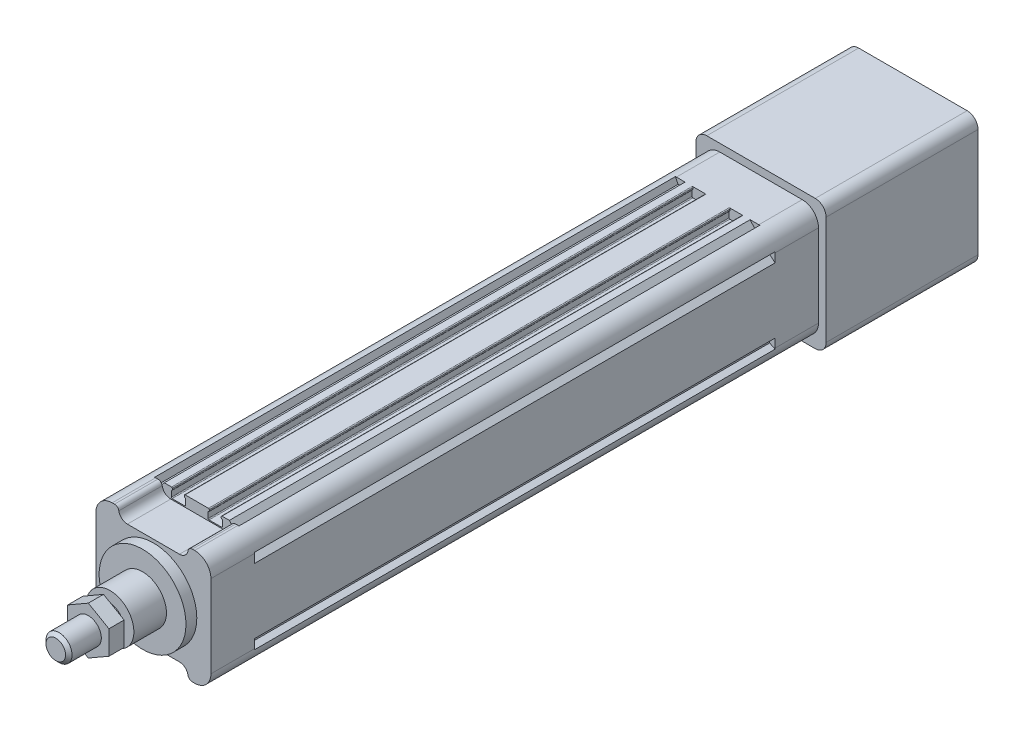
SolidWorks part; units mm, degrees
ref_plane "Front" through (0, 0, 0) normal (0, 0, 1) x (1, 0, 0)
ref_plane "Top" through (0, 0, 0) normal (0, 1, 0) x (1, 0, 0)
ref_plane "Right" through (0, 0, 0) normal (1, 0, 0) x (0, 0, -1)
sketch "草图1" plane through (0, 0, 0) normal (0, 0, 1) x (1, 0, 0)
  line L0 (19.7737, 3) -> (23.3, 3)
  line L1 (23.3, 3) -> (23.3, -3)
  line L2 (23.3, -3) -> (19.7737, -3)
  line L3 (-19.7737, -3) -> (-23.3, -3)
  line L4 (-23.3, -3) -> (-23.3, 3)
  line L5 (-23.3, 3) -> (-19.7737, 3)
  line L6 (-18.2, 24) -> (-19.4434, 26.4869)
  line L7 (-26.4869, 19.4434) -> (-24, 18.2)
  line L8 (-24, 18.2) -> (-24, 17.1)
  line L9 (-24, 17.1) -> (-26.5, 15)
  line L10 (-26.5, 15) -> (-26.5, -15)
  line L11 (-26.5, -15) -> (-24, -17.1)
  line L12 (-24, -17.1) -> (-24, -18.2)
  line L13 (-24, -18.2) -> (-26.4869, -19.4434)
  line L14 (-19.4434, -26.4869) -> (-18.2, -24)
  line L15 (-18.2, -24) -> (-17.1, -24)
  line L16 (-17.1, -24) -> (-15, -26.5)
  line L17 (-15, -26.5) -> (-11.65, -26.5)
  line L18 (-11.25, -26.1) -> (-11.25, -25.6)
  line L19 (-11.65, -25.2) -> (-11.75, -25.2)
  line L20 (-11.75, -25.2) -> (-11.75, -22.4)
  line L21 (-11.35, -22) -> (-5.65, -22)
  line L22 (-5.25, -22.4) -> (-5.25, -25.2)
  line L23 (-5.25, -25.2) -> (-5.35, -25.2)
  line L24 (-5.75, -25.6) -> (-5.75, -26.1)
  line L25 (-5.35, -26.5) -> (5.35, -26.5)
  line L26 (5.75, -26.1) -> (5.75, -25.6)
  line L27 (5.35, -25.2) -> (5.25, -25.2)
  line L28 (5.25, -25.2) -> (5.25, -22.4)
  line L29 (5.65, -22) -> (11.35, -22)
  line L30 (11.75, -22.4) -> (11.75, -25.2)
  line L31 (11.75, -25.2) -> (11.65, -25.2)
  line L32 (11.25, -25.6) -> (11.25, -26.1)
  line L33 (11.65, -26.5) -> (15, -26.5)
  line L34 (15, -26.5) -> (17.1, -24)
  line L35 (17.1, -24) -> (18.2, -24)
  line L36 (18.2, -24) -> (19.4434, -26.4869)
  line L37 (26.4869, -19.4434) -> (24, -18.2)
  line L38 (24, -18.2) -> (24, -17.1)
  line L39 (24, -17.1) -> (26.5, -15)
  line L40 (26.5, -15) -> (26.5, 15)
  line L41 (26.5, 15) -> (24, 17.1)
  line L42 (24, 17.1) -> (24, 18.2)
  line L43 (24, 18.2) -> (26.4869, 19.4434)
  line L44 (19.4434, 26.4869) -> (18.2, 24)
  line L45 (18.2, 24) -> (17.1, 24)
  line L46 (17.1, 24) -> (15, 26.5)
  line L47 (15, 26.5) -> (11.65, 26.5)
  line L48 (11.25, 26.1) -> (11.25, 25.6)
  line L49 (11.65, 25.2) -> (11.75, 25.2)
  line L50 (11.75, 25.2) -> (11.75, 22.4)
  line L51 (11.35, 22) -> (5.65, 22)
  line L52 (5.25, 22.4) -> (5.25, 25.2)
  line L53 (5.25, 25.2) -> (5.35, 25.2)
  line L54 (5.75, 25.6) -> (5.75, 26.1)
  line L55 (5.35, 26.5) -> (-5.35, 26.5)
  line L56 (-5.75, 26.1) -> (-5.75, 25.6)
  line L57 (-5.35, 25.2) -> (-5.25, 25.2)
  line L58 (-5.25, 25.2) -> (-5.25, 22.4)
  line L59 (-5.65, 22) -> (-11.35, 22)
  line L60 (-11.75, 22.4) -> (-11.75, 25.2)
  line L61 (-11.75, 25.2) -> (-11.65, 25.2)
  line L62 (-11.25, 25.6) -> (-11.25, 26.1)
  line L63 (-11.65, 26.5) -> (-15, 26.5)
  line L64 (-15, 26.5) -> (-17.1, 24)
  line L65 (-17.1, 24) -> (-18.2, 24)
  arc A0 (19.7737, 3) -> (-19.7737, 3) centre (0, 0) ccw
  arc A1 (-19.7737, -3) -> (19.7737, -3) centre (0, 0) ccw
  circle A2 centre (19, 19) radius 2.1
  circle A3 centre (19, -19) radius 2.1
  circle A4 centre (-19, -19) radius 2.1
  circle A5 centre (-19, 19) radius 2.1
  arc A6 (-19.4434, 26.4869) -> (-26.4869, 19.4434) centre (-19, 19) ccw
  arc A7 (-26.4869, -19.4434) -> (-19.4434, -26.4869) centre (-19, -19) ccw
  arc A8 (-11.65, -26.5) -> (-11.25, -26.1) centre (-11.65, -26.1) ccw
  arc A9 (-11.25, -25.6) -> (-11.65, -25.2) centre (-11.65, -25.6) ccw
  arc A10 (-11.35, -22) -> (-11.75, -22.4) centre (-11.35, -22.4) ccw
  arc A11 (-5.25, -22.4) -> (-5.65, -22) centre (-5.65, -22.4) ccw
  arc A12 (-5.35, -25.2) -> (-5.75, -25.6) centre (-5.35, -25.6) ccw
  arc A13 (-5.75, -26.1) -> (-5.35, -26.5) centre (-5.35, -26.1) ccw
  arc A14 (5.35, -26.5) -> (5.75, -26.1) centre (5.35, -26.1) ccw
  arc A15 (5.75, -25.6) -> (5.35, -25.2) centre (5.35, -25.6) ccw
  arc A16 (5.65, -22) -> (5.25, -22.4) centre (5.65, -22.4) ccw
  arc A17 (11.75, -22.4) -> (11.35, -22) centre (11.35, -22.4) ccw
  arc A18 (11.65, -25.2) -> (11.25, -25.6) centre (11.65, -25.6) ccw
  arc A19 (11.25, -26.1) -> (11.65, -26.5) centre (11.65, -26.1) ccw
  arc A20 (19.4434, -26.4869) -> (26.4869, -19.4434) centre (19, -19) ccw
  arc A21 (26.4869, 19.4434) -> (19.4434, 26.4869) centre (19, 19) ccw
  arc A22 (11.65, 26.5) -> (11.25, 26.1) centre (11.65, 26.1) ccw
  arc A23 (11.25, 25.6) -> (11.65, 25.2) centre (11.65, 25.6) ccw
  arc A24 (11.35, 22) -> (11.75, 22.4) centre (11.35, 22.4) ccw
  arc A25 (5.25, 22.4) -> (5.65, 22) centre (5.65, 22.4) ccw
  arc A26 (5.35, 25.2) -> (5.75, 25.6) centre (5.35, 25.6) ccw
  arc A27 (5.75, 26.1) -> (5.35, 26.5) centre (5.35, 26.1) ccw
  arc A28 (-5.35, 26.5) -> (-5.75, 26.1) centre (-5.35, 26.1) ccw
  arc A29 (-5.75, 25.6) -> (-5.35, 25.2) centre (-5.35, 25.6) ccw
  arc A30 (-5.65, 22) -> (-5.25, 22.4) centre (-5.65, 22.4) ccw
  arc A31 (-11.75, 22.4) -> (-11.35, 22) centre (-11.35, 22.4) ccw
  arc A32 (-11.65, 25.2) -> (-11.25, 25.6) centre (-11.65, 25.6) ccw
  arc A33 (-11.25, 26.1) -> (-11.65, 26.5) centre (-11.65, 26.1) ccw
extrude "凸台-拉伸1" add sketch "草图1" along normal blind 240
sketch "草图6" plane through (0, 0, 240) normal (0, 0, 1) x (1, 0, 0)
  line L0 (0, 0) -> (19, 0) construction
  line L2 (-26.5, -19) -> (-26.5, 19)
  line L3 (-19, 26.5) -> (-17.9161, 26.5)
  line L4 (26.5, -19) -> (26.5, 19)
  line L5 (-26.5, -26.5) -> (26.5, 26.5) construction
  line L6 (-26.5, 26.5) -> (26.5, -26.5) construction
  line L7 (-12, 21.5) -> (12, 21.5)
  line L9 (19, 26.5) -> (17.9161, 26.5)
  line L10 (19, -26.5) -> (17.9161, -26.5)
  line L11 (-12, -21.5) -> (12, -21.5)
  line L12 (-19, -26.5) -> (-17.9161, -26.5)
  arc A0 (12, 21.5) -> (15.9441, 24.8333) centre (12, 25.5) ccw
  arc A1 (-15.9441, 24.8333) -> (-12, 21.5) centre (-12, 25.5) ccw
  arc A2 (-15.9441, 24.8333) -> (-17.9161, 26.5) centre (-17.9161, 24.5) ccw
  arc A3 (15.9441, 24.8333) -> (17.9161, 26.5) centre (17.9161, 24.5) cw
  arc A4 (-26.5, -19) -> (-19, -26.5) centre (-19, -19) ccw
  arc A5 (19, -26.5) -> (26.5, -19) centre (19, -19) ccw
  arc A6 (26.5, 19) -> (19, 26.5) centre (19, 19) ccw
  arc A7 (-26.5, 19) -> (-19, 26.5) centre (-19, 19) cw
  arc A8 (15.9441, -24.8333) -> (17.9161, -26.5) centre (17.9161, -24.5) ccw
  arc A9 (12, -21.5) -> (15.9441, -24.8333) centre (12, -25.5) cw
  arc A10 (-15.9441, -24.8333) -> (-12, -21.5) centre (-12, -25.5) cw
  arc A11 (-15.9441, -24.8333) -> (-17.9161, -26.5) centre (-17.9161, -24.5) cw
  point P0 (0, 0)
  point P9 (0, 21.5)
  point P13 (20, 20.8461)
  point P16 (-12, 20.8461)
  dimension "D5" = 4
  dimension "D6" = 2
  dimension "D7" = 2
  dimension "D9" = 7.5
  dimension "D1" = 53
  dimension "D2" = 53
  dimension "D3" = 26.5
  dimension "D4" = 24
  dimension "D8" = 5
extrude "凸台-拉伸2" add sketch "草图6" along normal blind 20
sketch "草图7" plane through (0, 0, 260) normal (0, 0, 1) x (1, 0, 0)
  circle A0 centre (0, 0) radius 20
  dimension "D1" = 40
extrude "凸台-拉伸3" add sketch "草图7" along normal blind 5
sketch "草图9" plane through (0, 0, 265) normal (0, 0, 1) x (1, 0, 0)
  circle A0 centre (0, 0) radius 11
  dimension "D1" = 22
extrude "凸台-拉伸4" add sketch "草图9" along normal blind 15
sketch "草图10" plane through (0, 0, 280) normal (0, 0, 1) x (1, 0, 0)
  circle A0 centre (0, 0) radius 6
  dimension "D1" = 12
extrude "凸台-拉伸5" add sketch "草图10" along normal blind 25
sketch "草图11" plane through (0, 0, 0) normal (0, 0, -1) x (-1, 0, 0)
  line L1 (-19, -26.5) -> (19, -26.5)
  line L2 (-26.5, -19) -> (-26.5, 19)
  line L3 (-19, 26.5) -> (19, 26.5)
  line L4 (26.5, -19) -> (26.5, 19)
  line L5 (-26.5, -26.5) -> (26.5, 26.5) construction
  line L6 (-26.5, 26.5) -> (26.5, -26.5) construction
  arc A0 (-26.5, -19) -> (-19, -26.5) centre (-19, -19) ccw
  arc A1 (19, -26.5) -> (26.5, -19) centre (19, -19) ccw
  arc A2 (26.5, 19) -> (19, 26.5) centre (19, 19) ccw
  arc A3 (-26.5, 19) -> (-19, 26.5) centre (-19, 19) cw
  point P0 (0, 0)
  dimension "D3" = 7.5
  dimension "D1" = 53
  dimension "D2" = 53
extrude "凸台-拉伸6" add sketch "草图11" along normal blind 20
sketch "草图12" plane through (0, 0, -20) normal (0, 0, -1) x (-1, 0, 0)
  line L1 (-25, -30) -> (25, -30)
  line L2 (-30, -25) -> (-30, 25)
  line L3 (-25, 30) -> (25, 30)
  line L4 (30, -25) -> (30, 25)
  line L5 (-30, -30) -> (30, 30) construction
  line L6 (-30, 30) -> (30, -30) construction
  arc A0 (-30, -25) -> (-25, -30) centre (-25, -25) ccw
  arc A1 (25, -30) -> (30, -25) centre (25, -25) ccw
  arc A2 (30, 25) -> (25, 30) centre (25, 25) ccw
  arc A3 (-30, 25) -> (-25, 30) centre (-25, 25) cw
  point P0 (0, 0)
  dimension "D3" = 5
  dimension "D1" = 60
  dimension "D2" = 60
extrude "凸台-拉伸7" add sketch "草图12" along normal blind 70
sketch "草图14" plane through (0, 0, -90) normal (0, 0, -1) x (-1, 0, 0)
  circle A0 centre (0, 0) radius 19
  dimension "D1" = 38
extrude "切除-拉伸2" cut sketch "草图14" against normal blind 70
hole_wizard "M6 螺纹孔1" positions "草图15" profile "草图16" tap size "M6" standard "GB"
sketch "草图15" plane through (-26.5, 0, 0) normal (-1, 0, 0) x (0, 0, 1)
  line L0 (-20, -25) -> (-20, 25) construction
  line L1 (260, 19) -> (260, -19) construction
  point P0 (250, 11)
  point P2 (250, -11)
  point P4 (-10, 11)
  point P6 (-10, -11)
  dimension "D1" = 10
  dimension "D2" = 10
  dimension "D3" = 11
  dimension "D4" = 11
  dimension "D5" = 10
  dimension "D6" = 10
  dimension "D7" = 22
  dimension "D8" = 11
sketch "草图16" plane through (-26.5, 11, 250) normal (0, 1, 0) x (0, 0, 1)
  line L0 (0, 0) -> (0, 16.5022)
  line L1 (0, 16.5022) -> (2.5, 15)
  line L2 (2.5, 15) -> (2.5, 0)
  line L5 (2.5, 0) -> (0, 0)
  line L10 (0, 16.5022) -> (-2.5, 15) construction
  line L11 (0, -6.35) -> (0, 107.95) construction
  dimension "螺纹孔钻头直径" = 5
  dimension "螺纹孔钻头深度" = 15
  dimension "导头角度" = 118
cosmetic thread "孔螺蚊线4" parameters "D1"=12, "D2"=6
cosmetic thread "孔螺蚊线5" parameters "D1"=12, "D2"=6
cosmetic thread "孔螺蚊线6" parameters "D1"=12, "D2"=6
cosmetic thread "孔螺蚊线7" parameters "D1"=12, "D2"=6
chamfer "倒角1" distance 1.5 angle 45 1 edges at (6, 0, 305)
sketch "草图17" plane through (0, 0, 280) normal (0, 0, 1) x (1, 0, 0)
  line L1 (0, 10.9697) -> (-9.5, 5.4848)
  line L2 (-9.5, 5.4848) -> (-9.5, -5.4848)
  line L3 (-9.5, -5.4848) -> (0, -10.9697)
  line L4 (0, -10.9697) -> (9.5, -5.4848)
  line L5 (9.5, -5.4848) -> (9.5, 5.4848)
  line L6 (9.5, 5.4848) -> (0, 10.9697)
  circle A0 centre (0, 0) radius 9.5 construction
  dimension "D1" = 19
extrude "凸台-拉伸8" add sketch "草图17" along normal blind 7 from offset 3
